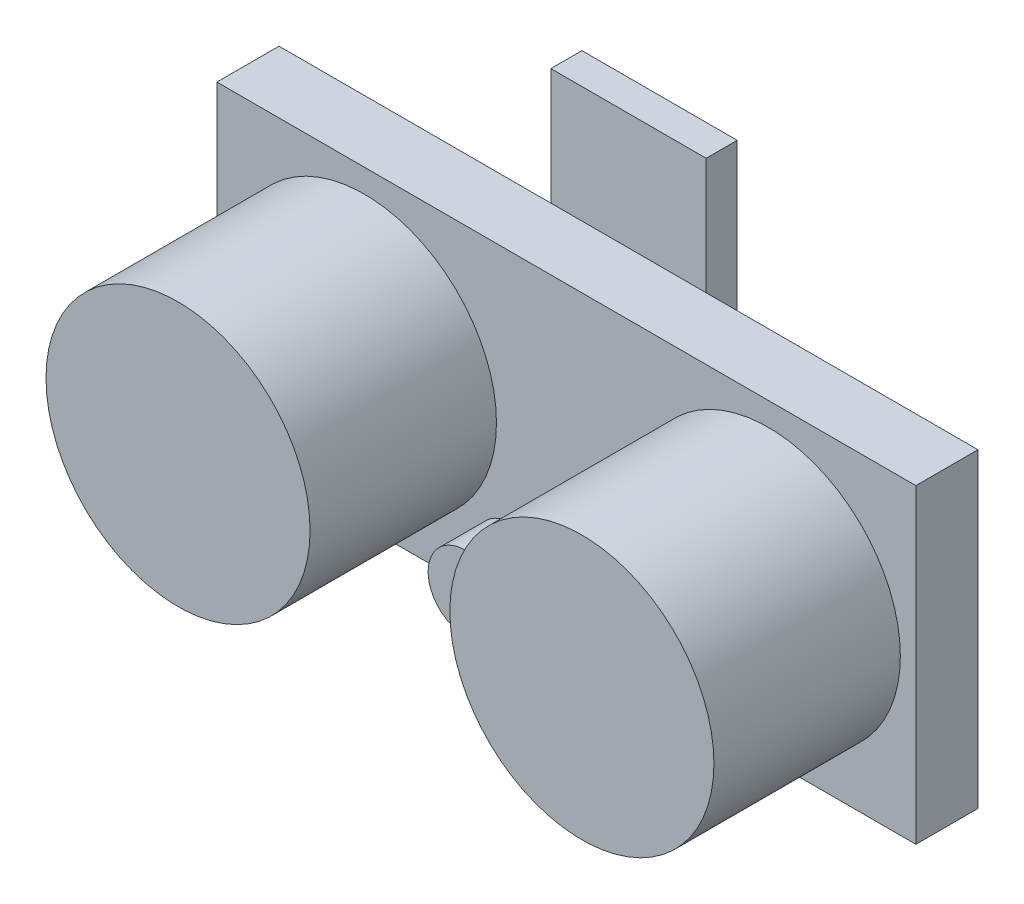
SolidWorks part; units mm, degrees
ref_plane "Front Plane" through (0, 0, 0) normal (0, 0, 1) x (1, 0, 0)
ref_plane "Top Plane" through (0, 0, 0) normal (0, 1, 0) x (1, 0, 0)
ref_plane "Right Plane" through (0, 0, 0) normal (1, 0, 0) x (0, 0, -1)
sketch "Sketch1" plane through (0, 0, 0) normal (0, 0, 1) x (1, 0, 0)
  line L1 (22.5, -10) -> (-22.5, -10)
  line L2 (22.5, -10) -> (22.5, 10)
  line L3 (22.5, 10) -> (-22.5, 10)
  line L4 (-22.5, -10) -> (-22.5, 10)
  line L5 (22.5, -10) -> (-22.5, 10) construction
  line L6 (22.5, 10) -> (-22.5, -10) construction
  point P0 (0, 0)
  dimension "D1" = 45
  dimension "D2" = 20
extrude "Boss-Extrude1" add sketch "Sketch1" along normal blind 4
sketch "Sketch2" plane through (0, 0, 0) normal (0, 0, -1) x (-1, 0, 0)
  line L5 (-22.5, 10) -> (22.5, 10) construction
  line L6 (-5, 17.5) -> (5, 17.5)
  line L7 (-5, 17.5) -> (-5, 7.5)
  line L8 (-5, 7.5) -> (5, 7.5)
  line L9 (5, 17.5) -> (5, 7.5)
  dimension "D1" = 10
  dimension "D2" = 5
  dimension "D3" = 10
  dimension "D4" = 2.5
extrude "Boss-Extrude2" add sketch "Sketch2" along normal blind 2
sketch "Sketch3" plane through (0, 0, 4) normal (0, 0, 1) x (1, 0, 0)
  line L0 (0, 10) -> (0, -10) construction
  line L1 (22.5, 10) -> (-22.5, 10) construction
  line L2 (-22.5, -10) -> (22.5, -10) construction
  circle A0 centre (-13, 0) radius 8.5
  circle A1 centre (13, 0) radius 8.5
  dimension "D2" = 17
  dimension "D1" = 13
extrude "Boss-Extrude3" add sketch "Sketch3" along normal blind 12
sketch "Sketch4" plane through (0, 0, 4) normal (0, 0, 1) x (1, 0, 0)
  line L0 (3.5, -7.5) -> (-3.5, -7.5) construction
  line L1 (3.5, -9.9) -> (-3.5, -9.9)
  line L2 (3.5, -5.1) -> (-3.5, -5.1)
  line L3 (-22.5, -10) -> (22.5, -10) construction
  arc A0 (3.5, -9.9) -> (3.5, -5.1) centre (3.5, -7.5) ccw
  arc A1 (-3.5, -5.1) -> (-3.5, -9.9) centre (-3.5, -7.5) ccw
  point P2 (0, -7.5)
  dimension "D1" = 4.8
  dimension "D2" = 7
  dimension "D3" = 0
  dimension "D4" = 2.5
extrude "Boss-Extrude4" add sketch "Sketch4" along normal blind 3
sketch "Sketch5" plane through (0, 0, 0) normal (0, 0, 1) x (1, 0, 0)
  line L0 (-5, 10) -> (5, 10) construction
  line L1 (5, 10) -> (5, 17.5) construction
  line L2 (5, 17.5) -> (-5, 17.5) construction
  line L3 (-5, 17.5) -> (-5, 10) construction
  line L4 (-22.5, 10) -> (-22.5, -10) construction
  line L5 (-22.5, -10) -> (22.5, -10) construction
  line L6 (22.5, -10) -> (22.5, 10) construction
  line L7 (22.5, 10) -> (-22.5, 10) construction
  line L8 (-5, 10) -> (5, 10)
  line L9 (5, 10) -> (5, 17.5)
  line L10 (5, 17.5) -> (-5, 17.5)
  line L11 (-5, 17.5) -> (-5, 10)
  line L12 (-22.5, 10) -> (-22.5, -10)
  line L13 (-22.5, -10) -> (22.5, -10)
  line L14 (22.5, -10) -> (22.5, 10)
  line L15 (22.5, 10) -> (-22.5, 10)
  line L16 (3.5, -5.1) -> (-3.5, -5.1) construction
  line L17 (-3.5, -9.9) -> (3.5, -9.9) construction
  line L18 (3.5, -5.1) -> (-3.5, -5.1)
  line L19 (-3.5, -9.9) -> (3.5, -9.9)
  circle A0 centre (13, 0) radius 8.5 construction
  arc A1 (3.5, -9.9) -> (3.5, -5.1) centre (3.5, -7.5) ccw construction
  arc A2 (-3.5, -5.1) -> (-3.5, -9.9) centre (-3.5, -7.5) ccw construction
  circle A3 centre (-13, 0) radius 8.5 construction
  circle A4 centre (13, 0) radius 8.5
  arc A5 (3.5, -9.9) -> (3.5, -5.1) centre (3.5, -7.5) ccw
  arc A6 (-3.5, -5.1) -> (-3.5, -9.9) centre (-3.5, -7.5) ccw
  circle A7 centre (-13, 0) radius 8.5
